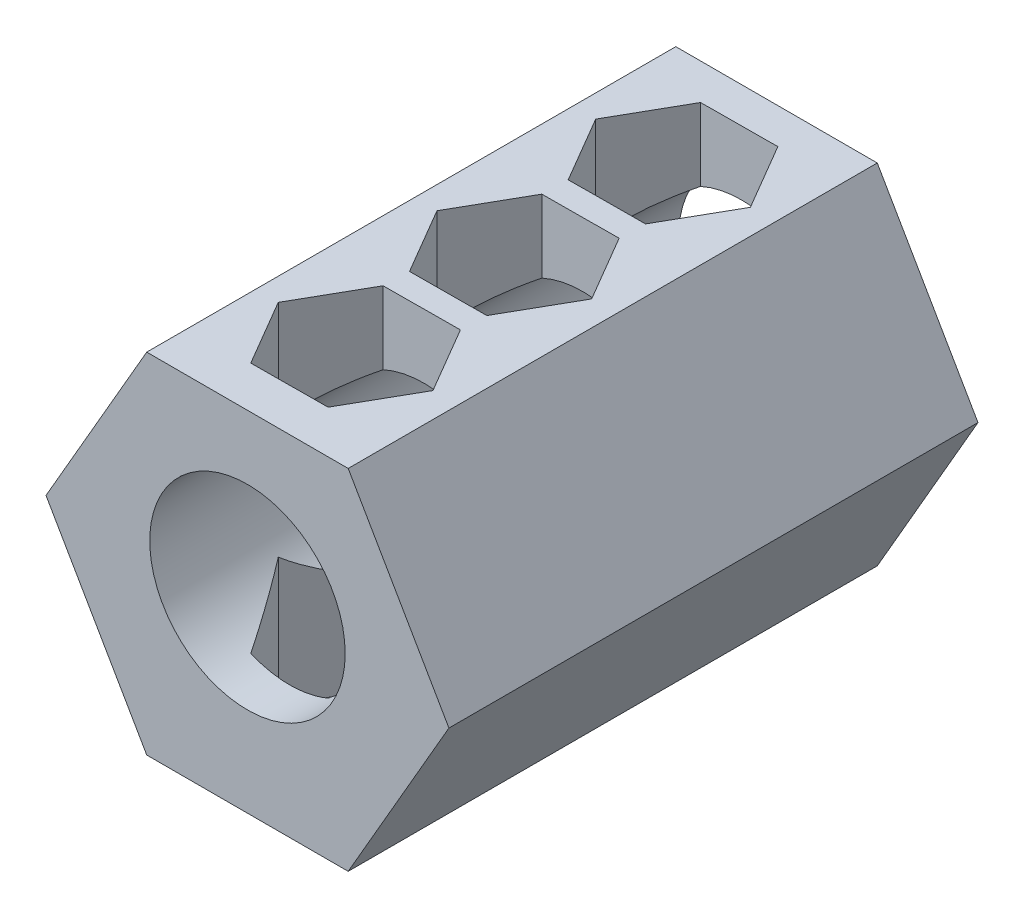
SolidWorks part; units mm, degrees
ref_plane "前视基准面" through (0, 0, 0) normal (0, 0, 1) x (1, 0, 0)
ref_plane "上视基准面" through (0, 0, 0) normal (0, 1, 0) x (1, 0, 0)
ref_plane "右视基准面" through (0, 0, 0) normal (1, 0, 0) x (0, 0, -1)
sketch "草图1" plane through (0, 0, 0) normal (0, 0, 1) x (1, 0, 0)
  line L7 (38.0784, 0) -> (19.0392, 32.9769)
  line L8 (19.0392, 32.9769) -> (-19.0392, 32.9769)
  line L9 (-19.0392, 32.9769) -> (-38.0784, 0)
  line L10 (-38.0784, 0) -> (-19.0392, -32.9769)
  line L11 (-19.0392, -32.9769) -> (19.0392, -32.9769)
  line L12 (19.0392, -32.9769) -> (38.0784, 0)
  circle A1 centre (0, 0) radius 32.9769 construction
extrude "凸台-拉伸1" add sketch "草图1" along normal blind 100 contours L7 L8 L9 L10 L11 L12
sketch "草图2" plane through (0, 0, 100) normal (0, 0, 1) x (1, 0, 0)
  circle A0 centre (0, 2.3894) radius 18.4695
extrude "切除-拉伸1" cut sketch "草图2" against normal blind 100 contours A0
sketch "草图7" plane through (0, 32.9769, 0) normal (0, 1, 0) x (1, 0, 0)
  line L0 (6.9646, -36.7149) -> (-7.5627, -36.8037)
  line L1 (6.9646, -6.7149) -> (-7.5627, -6.8037)
  line L2 (-7.5627, -6.8037) -> (-14.7494, -19.429)
  line L3 (-14.7494, -19.429) -> (-7.4089, -31.9656)
  line L4 (-7.4089, -31.9656) -> (7.1183, -31.8768)
  line L5 (7.1183, -31.8768) -> (14.3051, -19.2515)
  line L6 (14.3051, -19.2515) -> (6.9646, -6.7149)
  line L7 (-7.5627, -36.8037) -> (-14.7494, -49.429)
  line L8 (-14.7494, -49.429) -> (-7.4089, -61.9656)
  line L9 (-7.4089, -61.9656) -> (7.1183, -61.8768)
  line L10 (7.1183, -61.8768) -> (14.3051, -49.2515)
  line L11 (14.3051, -49.2515) -> (6.9646, -36.7149)
  line L12 (6.9646, -66.7149) -> (-7.5627, -66.8037)
  line L13 (-7.5627, -66.8037) -> (-14.7494, -79.429)
  line L14 (-14.7494, -79.429) -> (-7.4089, -91.9656)
  line L15 (-7.4089, -91.9656) -> (7.1183, -91.8768)
  line L16 (7.1183, -91.8768) -> (14.3051, -79.2515)
  line L17 (14.3051, -79.2515) -> (6.9646, -66.7149)
  circle A0 centre (-0.2222, -19.3402) radius 12.5812 construction
  dimension "D1" = 3
extrude "切除-拉伸6" cut sketch "草图7" against normal through all
